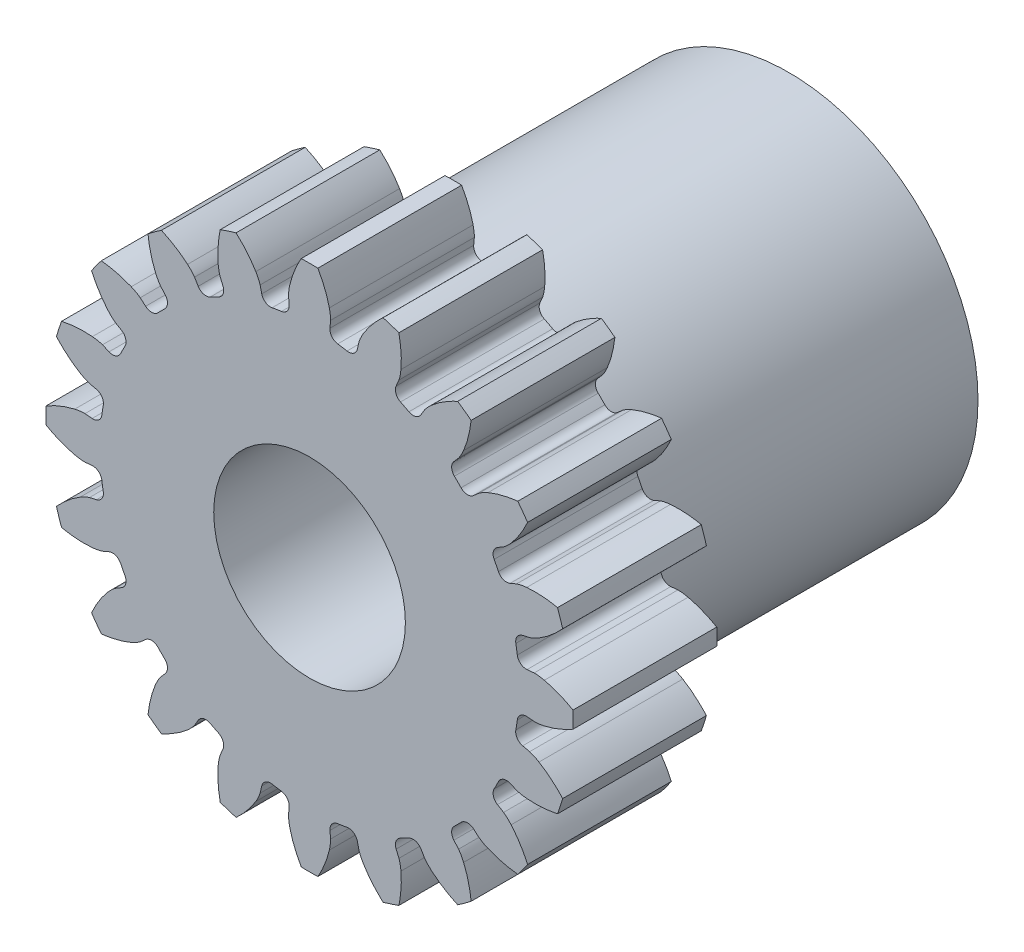
SolidWorks part; units mm, degrees
ref_plane "Front Plane" through (0, 0, 0) normal (0, 0, 1) x (1, 0, 0)
ref_plane "Top Plane" through (0, 0, 0) normal (0, 1, 0) x (1, 0, 0)
ref_plane "Right Plane" through (0, 0, 0) normal (1, 0, 0) x (0, 0, -1)
ref_plane "Plane1" through (0, 0, 0) normal (0, 0, -1) x (-1, 0, 0)
sketch "Sketch1" plane through (0, 0, 0) normal (0, 0, -1) x (-1, 0, 0)
  line L0 (-4.4476, -0.9979) -> (-4.5932, -1.031)
  line L1 (-4.3219, -1.8657) -> (-4.1847, -1.8069)
  line L2 (-3.9215, -2.3234) -> (-4.0498, -2.3999)
  line L3 (-3.5338, -3.11) -> (-3.4216, -3.0116)
  line L4 (-3.0116, -3.4216) -> (-3.11, -3.5338)
  line L5 (-2.3999, -4.0498) -> (-2.3234, -3.9215)
  line L6 (-1.8069, -4.1847) -> (-1.8657, -4.3219)
  line L7 (-1.031, -4.5932) -> (-0.9979, -4.4476)
  line L8 (-0.4253, -4.5383) -> (-0.4389, -4.6869)
  line L9 (0.4389, -4.6869) -> (0.4253, -4.5383)
  line L10 (0.9979, -4.4476) -> (1.031, -4.5932)
  line L11 (1.8657, -4.3219) -> (1.8069, -4.1847)
  line L12 (2.3234, -3.9215) -> (2.3999, -4.0498)
  line L13 (3.11, -3.5338) -> (3.0116, -3.4216)
  line L14 (3.4216, -3.0116) -> (3.5338, -3.11)
  line L15 (4.0498, -2.3999) -> (3.9215, -2.3234)
  line L16 (4.1847, -1.8069) -> (4.3219, -1.8657)
  line L17 (4.5932, -1.031) -> (4.4476, -0.9979)
  line L18 (4.5383, -0.4253) -> (4.6869, -0.4389)
  line L19 (4.6869, 0.4389) -> (4.5383, 0.4253)
  line L20 (4.4476, 0.9979) -> (4.5932, 1.031)
  line L21 (4.3219, 1.8657) -> (4.1847, 1.8069)
  line L22 (3.9215, 2.3234) -> (4.0498, 2.3999)
  line L23 (3.5338, 3.11) -> (3.4216, 3.0116)
  line L24 (3.0116, 3.4216) -> (3.11, 3.5338)
  line L25 (2.3999, 4.0498) -> (2.3234, 3.9215)
  line L26 (1.8069, 4.1847) -> (1.8657, 4.3219)
  line L27 (1.031, 4.5932) -> (0.9979, 4.4476)
  line L28 (0.4253, 4.5383) -> (0.4389, 4.6869)
  line L29 (-0.4389, 4.6869) -> (-0.4253, 4.5383)
  line L30 (-0.9979, 4.4476) -> (-1.031, 4.5932)
  line L31 (-1.8657, 4.3219) -> (-1.8069, 4.1847)
  line L32 (-2.3234, 3.9215) -> (-2.3999, 4.0498)
  line L33 (-3.11, 3.5338) -> (-3.0116, 3.4216)
  line L34 (-3.4216, 3.0116) -> (-3.5338, 3.11)
  line L35 (-4.0498, 2.3999) -> (-3.9215, 2.3234)
  line L36 (-4.1847, 1.8069) -> (-4.3219, 1.8657)
  line L37 (-4.5932, 1.031) -> (-4.4476, 0.9979)
  line L38 (-4.5383, 0.4253) -> (-4.6869, 0.4389)
  line L39 (-4.6869, -0.4389) -> (-4.5383, -0.4253)
  arc A0 (-4.3355, -0.5869) -> (-4.3046, -0.7816) centre (0, 0) ccw
  arc A1 (-4.3046, -0.7816) -> (-4.4476, -0.9979) centre (-4.4891, -0.8151) cw
  arc A2 (-5.2823, -1.5339) -> (-5.1751, -1.8639) centre (-0.0005, -0.0002) ccw
  arc A3 (-4.1847, -1.8069) -> (-3.9419, -1.8979) centre (-4.1108, -1.9792) cw
  arc A4 (-3.9419, -1.8979) -> (-3.8524, -2.0735) centre (0, 0) ccw
  arc A5 (-3.8524, -2.0735) -> (-3.9215, -2.3234) centre (-4.0175, -2.1624) cw
  arc A6 (-4.5498, -3.0912) -> (-4.3459, -3.3719) centre (-0.0004, -0.0003) ccw
  arc A7 (-3.4216, -3.0116) -> (-3.1625, -3.0231) centre (-3.298, -3.1527) cw
  arc A8 (-3.1625, -3.0231) -> (-3.0231, -3.1625) centre (0, 0) ccw
  arc A9 (-3.0231, -3.1625) -> (-3.0116, -3.4216) centre (-3.1527, -3.298) cw
  arc A10 (-3.3719, -4.3459) -> (-3.0912, -4.5498) centre (-0.0003, -0.0004) ccw
  arc A11 (-2.3234, -3.9215) -> (-2.0735, -3.8524) centre (-2.1624, -4.0175) cw
  arc A12 (-2.0735, -3.8524) -> (-1.8979, -3.9419) centre (0, 0) ccw
  arc A13 (-1.8979, -3.9419) -> (-1.8069, -4.1847) centre (-1.9792, -4.1108) cw
  arc A14 (-1.8639, -5.1751) -> (-1.5339, -5.2823) centre (-0.0002, -0.0005) ccw
  arc A15 (-0.9979, -4.4476) -> (-0.7816, -4.3046) centre (-0.8151, -4.4891) cw
  arc A16 (-0.7816, -4.3046) -> (-0.5869, -4.3355) centre (0, 0) ccw
  arc A17 (-0.5869, -4.3355) -> (-0.4253, -4.5383) centre (-0.612, -4.5213) cw
  arc A18 (-0.1735, -5.4978) -> (0.1735, -5.4978) centre (0, -0.0005) ccw
  arc A19 (0.4253, -4.5383) -> (0.5869, -4.3355) centre (0.612, -4.5213) cw
  arc A20 (0.5869, -4.3355) -> (0.7816, -4.3046) centre (0, 0) ccw
  arc A21 (0.7816, -4.3046) -> (0.9979, -4.4476) centre (0.8151, -4.4891) cw
  arc A22 (1.5339, -5.2823) -> (1.8639, -5.1751) centre (0.0002, -0.0005) ccw
  arc A23 (1.8069, -4.1847) -> (1.8979, -3.9419) centre (1.9792, -4.1108) cw
  arc A24 (1.8979, -3.9419) -> (2.0735, -3.8524) centre (0, 0) ccw
  arc A25 (2.0735, -3.8524) -> (2.3234, -3.9215) centre (2.1624, -4.0175) cw
  arc A26 (3.0912, -4.5498) -> (3.3719, -4.3459) centre (0.0003, -0.0004) ccw
  arc A27 (3.0116, -3.4216) -> (3.0231, -3.1625) centre (3.1527, -3.298) cw
  arc A28 (3.0231, -3.1625) -> (3.1625, -3.0231) centre (0, 0) ccw
  arc A29 (3.1625, -3.0231) -> (3.4216, -3.0116) centre (3.298, -3.1527) cw
  arc A30 (4.3459, -3.3719) -> (4.5498, -3.0912) centre (0.0004, -0.0003) ccw
  arc A31 (3.9215, -2.3234) -> (3.8524, -2.0735) centre (4.0175, -2.1624) cw
  arc A32 (3.8524, -2.0735) -> (3.9419, -1.8979) centre (0, 0) ccw
  arc A33 (3.9419, -1.8979) -> (4.1847, -1.8069) centre (4.1108, -1.9792) cw
  arc A34 (5.1751, -1.8639) -> (5.2823, -1.5339) centre (0.0005, -0.0002) ccw
  arc A35 (4.4476, -0.9979) -> (4.3046, -0.7816) centre (4.4891, -0.8151) cw
  arc A36 (4.3046, -0.7816) -> (4.3355, -0.5869) centre (0, 0) ccw
  arc A37 (4.3355, -0.5869) -> (4.5383, -0.4253) centre (4.5213, -0.612) cw
  arc A38 (5.4978, -0.1735) -> (5.4978, 0.1735) centre (0.0005, 0) ccw
  arc A39 (4.5383, 0.4253) -> (4.3355, 0.5869) centre (4.5213, 0.612) cw
  arc A40 (4.3355, 0.5869) -> (4.3046, 0.7816) centre (0, 0) ccw
  arc A41 (4.3046, 0.7816) -> (4.4476, 0.9979) centre (4.4891, 0.8151) cw
  arc A42 (5.2823, 1.5339) -> (5.1751, 1.8639) centre (0.0005, 0.0002) ccw
  arc A43 (4.1847, 1.8069) -> (3.9419, 1.8979) centre (4.1108, 1.9792) cw
  arc A44 (3.9419, 1.8979) -> (3.8524, 2.0735) centre (0, 0) ccw
  arc A45 (3.8524, 2.0735) -> (3.9215, 2.3234) centre (4.0175, 2.1624) cw
  arc A46 (4.5498, 3.0912) -> (4.3459, 3.3719) centre (0.0004, 0.0003) ccw
  arc A47 (3.4216, 3.0116) -> (3.1625, 3.0231) centre (3.298, 3.1527) cw
  arc A48 (3.1625, 3.0231) -> (3.0231, 3.1625) centre (0, 0) ccw
  arc A49 (3.0231, 3.1625) -> (3.0116, 3.4216) centre (3.1527, 3.298) cw
  arc A50 (3.3719, 4.3459) -> (3.0912, 4.5498) centre (0.0003, 0.0004) ccw
  arc A51 (2.3234, 3.9215) -> (2.0735, 3.8524) centre (2.1624, 4.0175) cw
  arc A52 (2.0735, 3.8524) -> (1.8979, 3.9419) centre (0, 0) ccw
  arc A53 (1.8979, 3.9419) -> (1.8069, 4.1847) centre (1.9792, 4.1108) cw
  arc A54 (1.8639, 5.1751) -> (1.5339, 5.2823) centre (0.0002, 0.0005) ccw
  arc A55 (0.9979, 4.4476) -> (0.7816, 4.3046) centre (0.8151, 4.4891) cw
  arc A56 (0.7816, 4.3046) -> (0.5869, 4.3355) centre (0, 0) ccw
  arc A57 (0.5869, 4.3355) -> (0.4253, 4.5383) centre (0.612, 4.5213) cw
  arc A58 (0.1735, 5.4978) -> (-0.1735, 5.4978) centre (0, 0.0005) ccw
  arc A59 (-0.4253, 4.5383) -> (-0.5869, 4.3355) centre (-0.612, 4.5213) cw
  arc A60 (-0.5869, 4.3355) -> (-0.7816, 4.3046) centre (0, 0) ccw
  arc A61 (-0.7816, 4.3046) -> (-0.9979, 4.4476) centre (-0.8151, 4.4891) cw
  arc A62 (-1.5339, 5.2823) -> (-1.8639, 5.1751) centre (-0.0002, 0.0005) ccw
  arc A63 (-1.8069, 4.1847) -> (-1.8979, 3.9419) centre (-1.9792, 4.1108) cw
  arc A64 (-1.8979, 3.9419) -> (-2.0735, 3.8524) centre (0, 0) ccw
  arc A65 (-2.0735, 3.8524) -> (-2.3234, 3.9215) centre (-2.1624, 4.0175) cw
  arc A66 (-3.0912, 4.5498) -> (-3.3719, 4.3459) centre (-0.0003, 0.0004) ccw
  arc A67 (-3.0116, 3.4216) -> (-3.0231, 3.1625) centre (-3.1527, 3.298) cw
  arc A68 (-3.0231, 3.1625) -> (-3.1625, 3.0231) centre (0, 0) ccw
  arc A69 (-3.1625, 3.0231) -> (-3.4216, 3.0116) centre (-3.298, 3.1527) cw
  arc A70 (-4.3459, 3.3719) -> (-4.5498, 3.0912) centre (-0.0004, 0.0003) ccw
  arc A71 (-3.9215, 2.3234) -> (-3.8524, 2.0735) centre (-4.0175, 2.1624) cw
  arc A72 (-3.8524, 2.0735) -> (-3.9419, 1.8979) centre (0, 0) ccw
  arc A73 (-3.9419, 1.8979) -> (-4.1847, 1.8069) centre (-4.1108, 1.9792) cw
  arc A74 (-5.1751, 1.8639) -> (-5.2823, 1.5339) centre (-0.0005, 0.0002) ccw
  arc A75 (-4.4476, 0.9979) -> (-4.3046, 0.7816) centre (-4.4891, 0.8151) cw
  arc A76 (-4.3046, 0.7816) -> (-4.3355, 0.5869) centre (0, 0) ccw
  arc A77 (-4.3355, 0.5869) -> (-4.5383, 0.4253) centre (-4.5213, 0.612) cw
  arc A78 (-5.4978, 0.1735) -> (-5.4978, -0.1735) centre (-0.0005, 0) ccw
  arc A79 (-4.5383, -0.4253) -> (-4.3355, -0.5869) centre (-4.5213, -0.612) cw
  spline S0 degree 3 poles (-4.5932, -1.031) (-4.6077, -1.0352) (-4.6221, -1.0404) (-4.6362, -1.0459) (-4.6624, -1.0562) (-4.6881, -1.068) (-4.7133, -1.0806) (-4.7387, -1.0933) (-4.7636, -1.1069) (-4.7881, -1.1212) knots 0 0 0 0 0.000046 0.000046 0.000046 0.00013 0.00013 0.00013 0.000215 0.000215 0.000215 0.000215
  spline S1 degree 3 poles (-4.7881, -1.1212) (-4.8505, -1.1578) (-4.9104, -1.1989) (-4.9678, -1.2429) (-5.0243, -1.2863) (-5.0786, -1.3326) (-5.1307, -1.3811) (-5.1833, -1.4299) (-5.2338, -1.4811) (-5.2823, -1.5339) knots 0 0 0 0 0.000217 0.000217 0.000217 0.000431 0.000431 0.000431 0.000646 0.000646 0.000646 0.000646
  spline S2 degree 3 poles (-5.1751, -1.8639) (-5.1043, -1.8782) (-5.0329, -1.89) (-4.9612, -1.8986) (-4.8905, -1.9071) (-4.8194, -1.9127) (-4.7483, -1.9145) (-4.6764, -1.9163) (-4.6042, -1.9144) (-4.5327, -1.9074) knots 0 0 0 0 0.000217 0.000217 0.000217 0.00043 0.00043 0.00043 0.000646 0.000646 0.000646 0.000646
  spline S3 degree 3 poles (-4.5327, -1.9074) (-4.5025, -1.9043) (-4.4723, -1.9004) (-4.4424, -1.8952) (-4.4221, -1.8918) (-4.4018, -1.8877) (-4.3817, -1.883) (-4.3616, -1.8782) (-4.3414, -1.8728) (-4.3219, -1.8657) knots 0 0 0 0 0.000091 0.000091 0.000091 0.000153 0.000153 0.000153 0.000215 0.000215 0.000215 0.000215
  spline S4 degree 3 poles (-4.0498, -2.3999) (-4.0623, -2.4084) (-4.0743, -2.4177) (-4.0861, -2.4274) (-4.1079, -2.4453) (-4.1286, -2.4644) (-4.1487, -2.4842) (-4.1689, -2.5041) (-4.1884, -2.5247) (-4.2073, -2.5459) knots 0 0 0 0 0.000046 0.000046 0.000046 0.00013 0.00013 0.00013 0.000215 0.000215 0.000215 0.000215
  spline S5 degree 3 poles (-4.2073, -2.5459) (-4.2554, -2.6) (-4.2996, -2.6576) (-4.3406, -2.7172) (-4.3809, -2.7759) (-4.4182, -2.8367) (-4.4528, -2.899) (-4.4877, -2.9617) (-4.5199, -3.0259) (-4.5498, -3.0912) knots 0 0 0 0 0.000217 0.000217 0.000217 0.000431 0.000431 0.000431 0.000646 0.000646 0.000646 0.000646
  spline S6 degree 3 poles (-4.3459, -3.3719) (-4.2741, -3.3636) (-4.2025, -3.3527) (-4.1316, -3.3388) (-4.0618, -3.325) (-3.9925, -3.3083) (-3.9243, -3.2881) (-3.8554, -3.2676) (-3.7873, -3.2435) (-3.7214, -3.2147) knots 0 0 0 0 0.000217 0.000217 0.000217 0.00043 0.00043 0.00043 0.000646 0.000646 0.000646 0.000646
  spline S7 degree 3 poles (-3.7214, -3.2147) (-3.6936, -3.2024) (-3.6662, -3.1894) (-3.6393, -3.1753) (-3.6211, -3.1657) (-3.603, -3.1556) (-3.5854, -3.1448) (-3.5677, -3.134) (-3.5502, -3.1227) (-3.5338, -3.11) knots 0 0 0 0 0.000091 0.000091 0.000091 0.000153 0.000153 0.000153 0.000215 0.000215 0.000215 0.000215
  spline S8 degree 3 poles (-3.11, -3.5338) (-3.1193, -3.5458) (-3.1278, -3.5584) (-3.136, -3.5712) (-3.1512, -3.595) (-3.165, -3.6196) (-3.178, -3.6446) (-3.1911, -3.6698) (-3.2032, -3.6955) (-3.2147, -3.7214) knots 0 0 0 0 0.000046 0.000046 0.000046 0.00013 0.00013 0.00013 0.000215 0.000215 0.000215 0.000215
  spline S9 degree 3 poles (-3.2147, -3.7214) (-3.2436, -3.7877) (-3.2679, -3.8562) (-3.2884, -3.9256) (-3.3087, -3.9938) (-3.3254, -4.0632) (-3.3391, -4.1331) (-3.3529, -4.2035) (-3.3637, -4.2746) (-3.3719, -4.3459) knots 0 0 0 0 0.000217 0.000217 0.000217 0.000431 0.000431 0.000431 0.000646 0.000646 0.000646 0.000646
  spline S10 degree 3 poles (-3.0912, -4.5498) (-3.0255, -4.5197) (-2.9608, -4.4873) (-2.8977, -4.4521) (-2.8355, -4.4175) (-2.7748, -4.3802) (-2.7162, -4.3398) (-2.6569, -4.299) (-2.5997, -4.2551) (-2.5459, -4.2073) knots 0 0 0 0 0.000217 0.000217 0.000217 0.00043 0.00043 0.00043 0.000646 0.000646 0.000646 0.000646
  spline S11 degree 3 poles (-2.5459, -4.2073) (-2.5233, -4.1871) (-2.5012, -4.1662) (-2.48, -4.1445) (-2.4656, -4.1297) (-2.4516, -4.1145) (-2.4381, -4.0989) (-2.4246, -4.0831) (-2.4115, -4.0669) (-2.3999, -4.0498) knots 0 0 0 0 0.000091 0.000091 0.000091 0.000153 0.000153 0.000153 0.000215 0.000215 0.000215 0.000215
  spline S12 degree 3 poles (-1.8657, -4.3219) (-1.8709, -4.3362) (-1.8751, -4.3508) (-1.8789, -4.3655) (-1.886, -4.3928) (-1.8916, -4.4205) (-1.8962, -4.4483) (-1.9009, -4.4763) (-1.9045, -4.5045) (-1.9074, -4.5327) knots 0 0 0 0 0.000046 0.000046 0.000046 0.00013 0.00013 0.00013 0.000215 0.000215 0.000215 0.000215
  spline S13 degree 3 poles (-1.9074, -4.5327) (-1.9144, -4.6047) (-1.9163, -4.6773) (-1.9144, -4.7496) (-1.9126, -4.8208) (-1.907, -4.8919) (-1.8984, -4.9626) (-1.8898, -5.0339) (-1.8781, -5.1048) (-1.8639, -5.1751) knots 0 0 0 0 0.000217 0.000217 0.000217 0.000431 0.000431 0.000431 0.000646 0.000646 0.000646 0.000646
  spline S14 degree 3 poles (-1.5339, -5.2823) (-1.4807, -5.2335) (-1.4292, -5.1826) (-1.3801, -5.1297) (-1.3317, -5.0775) (-1.2854, -5.0232) (-1.2421, -4.9668) (-1.1984, -4.9097) (-1.1575, -4.8502) (-1.1212, -4.7881) knots 0 0 0 0 0.000217 0.000217 0.000217 0.00043 0.00043 0.00043 0.000646 0.000646 0.000646 0.000646
  spline S15 degree 3 poles (-1.1212, -4.7881) (-1.1059, -4.7619) (-1.0914, -4.7352) (-1.0779, -4.708) (-1.0688, -4.6895) (-1.0601, -4.6707) (-1.0522, -4.6517) (-1.0442, -4.6325) (-1.0367, -4.6131) (-1.031, -4.5932) knots 0 0 0 0 0.000091 0.000091 0.000091 0.000153 0.000153 0.000153 0.000215 0.000215 0.000215 0.000215
  spline S16 degree 3 poles (-0.4389, -4.6869) (-0.4394, -4.7021) (-0.4389, -4.7173) (-0.438, -4.7325) (-0.4363, -4.7606) (-0.433, -4.7887) (-0.4288, -4.8166) (-0.4246, -4.8446) (-0.4193, -4.8725) (-0.4133, -4.9002) knots 0 0 0 0 0.000046 0.000046 0.000046 0.00013 0.00013 0.00013 0.000215 0.000215 0.000215 0.000215
  spline S17 degree 3 poles (-0.4133, -4.9002) (-0.3978, -4.9709) (-0.3772, -5.0405) (-0.353, -5.1087) (-0.3293, -5.1759) (-0.302, -5.2418) (-0.272, -5.3064) (-0.2418, -5.3715) (-0.2087, -5.4353) (-0.1735, -5.4978) knots 0 0 0 0 0.000217 0.000217 0.000217 0.000431 0.000431 0.000431 0.000646 0.000646 0.000646 0.000646
  spline S18 degree 3 poles (0.1735, -5.4978) (0.209, -5.4349) (0.2422, -5.3706) (0.2726, -5.3051) (0.3025, -5.2405) (0.3298, -5.1746) (0.3535, -5.1075) (0.3774, -5.0397) (0.3979, -4.9705) (0.4133, -4.9002) knots 0 0 0 0 0.000217 0.000217 0.000217 0.00043 0.00043 0.00043 0.000646 0.000646 0.000646 0.000646
  spline S19 degree 3 poles (0.4133, -4.9002) (0.4198, -4.8706) (0.4253, -4.8407) (0.4297, -4.8107) (0.4327, -4.7902) (0.4351, -4.7697) (0.4368, -4.7492) (0.4385, -4.7285) (0.4395, -4.7077) (0.4389, -4.6869) knots 0 0 0 0 0.000091 0.000091 0.000091 0.000153 0.000153 0.000153 0.000215 0.000215 0.000215 0.000215
  spline S20 degree 3 poles (1.031, -4.5932) (1.0352, -4.6077) (1.0404, -4.6221) (1.0459, -4.6362) (1.0562, -4.6624) (1.068, -4.6881) (1.0806, -4.7133) (1.0933, -4.7387) (1.1069, -4.7636) (1.1212, -4.7881) knots 0 0 0 0 0.000046 0.000046 0.000046 0.00013 0.00013 0.00013 0.000215 0.000215 0.000215 0.000215
  spline S21 degree 3 poles (1.1212, -4.7881) (1.1578, -4.8505) (1.1989, -4.9104) (1.2429, -4.9678) (1.2863, -5.0243) (1.3326, -5.0786) (1.3811, -5.1307) (1.4299, -5.1833) (1.4811, -5.2338) (1.5339, -5.2823) knots 0 0 0 0 0.000217 0.000217 0.000217 0.000431 0.000431 0.000431 0.000646 0.000646 0.000646 0.000646
  spline S22 degree 3 poles (1.8639, -5.1751) (1.8782, -5.1043) (1.89, -5.0329) (1.8986, -4.9612) (1.9071, -4.8905) (1.9127, -4.8194) (1.9145, -4.7483) (1.9163, -4.6764) (1.9144, -4.6042) (1.9074, -4.5327) knots 0 0 0 0 0.000217 0.000217 0.000217 0.00043 0.00043 0.00043 0.000646 0.000646 0.000646 0.000646
  spline S23 degree 3 poles (1.9074, -4.5327) (1.9043, -4.5025) (1.9004, -4.4723) (1.8952, -4.4424) (1.8918, -4.4221) (1.8877, -4.4018) (1.883, -4.3817) (1.8782, -4.3616) (1.8728, -4.3414) (1.8657, -4.3219) knots 0 0 0 0 0.000091 0.000091 0.000091 0.000153 0.000153 0.000153 0.000215 0.000215 0.000215 0.000215
  spline S24 degree 3 poles (2.3999, -4.0498) (2.4084, -4.0623) (2.4177, -4.0743) (2.4274, -4.0861) (2.4453, -4.1079) (2.4644, -4.1286) (2.4842, -4.1487) (2.5041, -4.1689) (2.5247, -4.1884) (2.5459, -4.2073) knots 0 0 0 0 0.000046 0.000046 0.000046 0.00013 0.00013 0.00013 0.000215 0.000215 0.000215 0.000215
  spline S25 degree 3 poles (2.5459, -4.2073) (2.6, -4.2554) (2.6576, -4.2996) (2.7172, -4.3406) (2.7759, -4.3809) (2.8367, -4.4182) (2.899, -4.4528) (2.9617, -4.4877) (3.0259, -4.5199) (3.0912, -4.5498) knots 0 0 0 0 0.000217 0.000217 0.000217 0.000431 0.000431 0.000431 0.000646 0.000646 0.000646 0.000646
  spline S26 degree 3 poles (3.3719, -4.3459) (3.3636, -4.2741) (3.3527, -4.2025) (3.3388, -4.1316) (3.325, -4.0618) (3.3083, -3.9925) (3.2881, -3.9243) (3.2676, -3.8554) (3.2435, -3.7873) (3.2147, -3.7214) knots 0 0 0 0 0.000217 0.000217 0.000217 0.00043 0.00043 0.00043 0.000646 0.000646 0.000646 0.000646
  spline S27 degree 3 poles (3.2147, -3.7214) (3.2024, -3.6936) (3.1894, -3.6662) (3.1753, -3.6393) (3.1657, -3.6211) (3.1556, -3.603) (3.1448, -3.5854) (3.134, -3.5677) (3.1227, -3.5502) (3.11, -3.5338) knots 0 0 0 0 0.000091 0.000091 0.000091 0.000153 0.000153 0.000153 0.000215 0.000215 0.000215 0.000215
  spline S28 degree 3 poles (3.5338, -3.11) (3.5458, -3.1193) (3.5584, -3.1278) (3.5712, -3.136) (3.595, -3.1512) (3.6196, -3.165) (3.6446, -3.178) (3.6698, -3.1911) (3.6955, -3.2032) (3.7214, -3.2147) knots 0 0 0 0 0.000046 0.000046 0.000046 0.00013 0.00013 0.00013 0.000215 0.000215 0.000215 0.000215
  spline S29 degree 3 poles (3.7214, -3.2147) (3.7877, -3.2436) (3.8562, -3.2679) (3.9256, -3.2884) (3.9938, -3.3087) (4.0632, -3.3254) (4.1331, -3.3391) (4.2035, -3.3529) (4.2746, -3.3637) (4.3459, -3.3719) knots 0 0 0 0 0.000217 0.000217 0.000217 0.000431 0.000431 0.000431 0.000646 0.000646 0.000646 0.000646
  spline S30 degree 3 poles (4.5498, -3.0912) (4.5197, -3.0255) (4.4873, -2.9608) (4.4521, -2.8977) (4.4175, -2.8355) (4.3802, -2.7748) (4.3398, -2.7162) (4.299, -2.6569) (4.2551, -2.5997) (4.2073, -2.5459) knots 0 0 0 0 0.000217 0.000217 0.000217 0.00043 0.00043 0.00043 0.000646 0.000646 0.000646 0.000646
  spline S31 degree 3 poles (4.2073, -2.5459) (4.1871, -2.5233) (4.1662, -2.5012) (4.1445, -2.48) (4.1297, -2.4656) (4.1145, -2.4516) (4.0989, -2.4381) (4.0831, -2.4246) (4.0669, -2.4115) (4.0498, -2.3999) knots 0 0 0 0 0.000091 0.000091 0.000091 0.000153 0.000153 0.000153 0.000215 0.000215 0.000215 0.000215
  spline S32 degree 3 poles (4.3219, -1.8657) (4.3362, -1.8709) (4.3508, -1.8751) (4.3655, -1.8789) (4.3928, -1.886) (4.4205, -1.8916) (4.4483, -1.8962) (4.4763, -1.9009) (4.5045, -1.9045) (4.5327, -1.9074) knots 0 0 0 0 0.000046 0.000046 0.000046 0.00013 0.00013 0.00013 0.000215 0.000215 0.000215 0.000215
  spline S33 degree 3 poles (4.5327, -1.9074) (4.6047, -1.9144) (4.6773, -1.9163) (4.7496, -1.9144) (4.8208, -1.9126) (4.8919, -1.907) (4.9626, -1.8984) (5.0339, -1.8898) (5.1048, -1.8781) (5.1751, -1.8639) knots 0 0 0 0 0.000217 0.000217 0.000217 0.000431 0.000431 0.000431 0.000646 0.000646 0.000646 0.000646
  spline S34 degree 3 poles (5.2823, -1.5339) (5.2335, -1.4807) (5.1826, -1.4292) (5.1297, -1.3801) (5.0775, -1.3317) (5.0232, -1.2854) (4.9668, -1.2421) (4.9097, -1.1984) (4.8502, -1.1575) (4.7881, -1.1212) knots 0 0 0 0 0.000217 0.000217 0.000217 0.00043 0.00043 0.00043 0.000646 0.000646 0.000646 0.000646
  spline S35 degree 3 poles (4.7881, -1.1212) (4.7619, -1.1059) (4.7352, -1.0914) (4.708, -1.0779) (4.6895, -1.0688) (4.6707, -1.0601) (4.6517, -1.0522) (4.6325, -1.0442) (4.6131, -1.0367) (4.5932, -1.031) knots 0 0 0 0 0.000091 0.000091 0.000091 0.000153 0.000153 0.000153 0.000215 0.000215 0.000215 0.000215
  spline S36 degree 3 poles (4.6869, -0.4389) (4.7021, -0.4394) (4.7173, -0.4389) (4.7325, -0.438) (4.7606, -0.4363) (4.7887, -0.433) (4.8166, -0.4288) (4.8446, -0.4246) (4.8725, -0.4193) (4.9002, -0.4133) knots 0 0 0 0 0.000046 0.000046 0.000046 0.00013 0.00013 0.00013 0.000215 0.000215 0.000215 0.000215
  spline S37 degree 3 poles (4.9002, -0.4133) (4.9709, -0.3978) (5.0405, -0.3772) (5.1087, -0.353) (5.1759, -0.3293) (5.2418, -0.302) (5.3064, -0.272) (5.3715, -0.2418) (5.4353, -0.2087) (5.4978, -0.1735) knots 0 0 0 0 0.000217 0.000217 0.000217 0.000431 0.000431 0.000431 0.000646 0.000646 0.000646 0.000646
  spline S38 degree 3 poles (5.4978, 0.1735) (5.4349, 0.209) (5.3706, 0.2422) (5.3051, 0.2726) (5.2405, 0.3025) (5.1746, 0.3298) (5.1075, 0.3535) (5.0397, 0.3774) (4.9705, 0.3979) (4.9002, 0.4133) knots 0 0 0 0 0.000217 0.000217 0.000217 0.00043 0.00043 0.00043 0.000646 0.000646 0.000646 0.000646
  spline S39 degree 3 poles (4.9002, 0.4133) (4.8706, 0.4198) (4.8407, 0.4253) (4.8107, 0.4297) (4.7902, 0.4327) (4.7697, 0.4351) (4.7492, 0.4368) (4.7285, 0.4385) (4.7077, 0.4395) (4.6869, 0.4389) knots 0 0 0 0 0.000091 0.000091 0.000091 0.000153 0.000153 0.000153 0.000215 0.000215 0.000215 0.000215
  spline S40 degree 3 poles (4.5932, 1.031) (4.6077, 1.0352) (4.6221, 1.0404) (4.6362, 1.0459) (4.6624, 1.0562) (4.6881, 1.068) (4.7133, 1.0806) (4.7387, 1.0933) (4.7636, 1.1069) (4.7881, 1.1212) knots 0 0 0 0 0.000046 0.000046 0.000046 0.00013 0.00013 0.00013 0.000215 0.000215 0.000215 0.000215
  spline S41 degree 3 poles (4.7881, 1.1212) (4.8505, 1.1578) (4.9104, 1.1989) (4.9678, 1.2429) (5.0243, 1.2863) (5.0786, 1.3326) (5.1307, 1.3811) (5.1833, 1.4299) (5.2338, 1.4811) (5.2823, 1.5339) knots 0 0 0 0 0.000217 0.000217 0.000217 0.000431 0.000431 0.000431 0.000646 0.000646 0.000646 0.000646
  spline S42 degree 3 poles (5.1751, 1.8639) (5.1043, 1.8782) (5.0329, 1.89) (4.9612, 1.8986) (4.8905, 1.9071) (4.8194, 1.9127) (4.7483, 1.9145) (4.6764, 1.9163) (4.6042, 1.9144) (4.5327, 1.9074) knots 0 0 0 0 0.000217 0.000217 0.000217 0.00043 0.00043 0.00043 0.000646 0.000646 0.000646 0.000646
  spline S43 degree 3 poles (4.5327, 1.9074) (4.5025, 1.9043) (4.4723, 1.9004) (4.4424, 1.8952) (4.4221, 1.8918) (4.4018, 1.8877) (4.3817, 1.883) (4.3616, 1.8782) (4.3414, 1.8728) (4.3219, 1.8657) knots 0 0 0 0 0.000091 0.000091 0.000091 0.000153 0.000153 0.000153 0.000215 0.000215 0.000215 0.000215
  spline S44 degree 3 poles (4.0498, 2.3999) (4.0623, 2.4084) (4.0743, 2.4177) (4.0861, 2.4274) (4.1079, 2.4453) (4.1286, 2.4644) (4.1487, 2.4842) (4.1689, 2.5041) (4.1884, 2.5247) (4.2073, 2.5459) knots 0 0 0 0 0.000046 0.000046 0.000046 0.00013 0.00013 0.00013 0.000215 0.000215 0.000215 0.000215
  spline S45 degree 3 poles (4.2073, 2.5459) (4.2554, 2.6) (4.2996, 2.6576) (4.3406, 2.7172) (4.3809, 2.7759) (4.4182, 2.8367) (4.4528, 2.899) (4.4877, 2.9617) (4.5199, 3.0259) (4.5498, 3.0912) knots 0 0 0 0 0.000217 0.000217 0.000217 0.000431 0.000431 0.000431 0.000646 0.000646 0.000646 0.000646
  spline S46 degree 3 poles (4.3459, 3.3719) (4.2741, 3.3636) (4.2025, 3.3527) (4.1316, 3.3388) (4.0618, 3.325) (3.9925, 3.3083) (3.9243, 3.2881) (3.8554, 3.2676) (3.7873, 3.2435) (3.7214, 3.2147) knots 0 0 0 0 0.000217 0.000217 0.000217 0.00043 0.00043 0.00043 0.000646 0.000646 0.000646 0.000646
  spline S47 degree 3 poles (3.7214, 3.2147) (3.6936, 3.2024) (3.6662, 3.1894) (3.6393, 3.1753) (3.6211, 3.1657) (3.603, 3.1556) (3.5854, 3.1448) (3.5677, 3.134) (3.5502, 3.1227) (3.5338, 3.11) knots 0 0 0 0 0.000091 0.000091 0.000091 0.000153 0.000153 0.000153 0.000215 0.000215 0.000215 0.000215
  spline S48 degree 3 poles (3.11, 3.5338) (3.1193, 3.5458) (3.1278, 3.5584) (3.136, 3.5712) (3.1512, 3.595) (3.165, 3.6196) (3.178, 3.6446) (3.1911, 3.6698) (3.2032, 3.6955) (3.2147, 3.7214) knots 0 0 0 0 0.000046 0.000046 0.000046 0.00013 0.00013 0.00013 0.000215 0.000215 0.000215 0.000215
  spline S49 degree 3 poles (3.2147, 3.7214) (3.2436, 3.7877) (3.2679, 3.8562) (3.2884, 3.9256) (3.3087, 3.9938) (3.3254, 4.0632) (3.3391, 4.1331) (3.3529, 4.2035) (3.3637, 4.2746) (3.3719, 4.3459) knots 0 0 0 0 0.000217 0.000217 0.000217 0.000431 0.000431 0.000431 0.000646 0.000646 0.000646 0.000646
  spline S50 degree 3 poles (3.0912, 4.5498) (3.0255, 4.5197) (2.9608, 4.4873) (2.8977, 4.4521) (2.8355, 4.4175) (2.7748, 4.3802) (2.7162, 4.3398) (2.6569, 4.299) (2.5997, 4.2551) (2.5459, 4.2073) knots 0 0 0 0 0.000217 0.000217 0.000217 0.00043 0.00043 0.00043 0.000646 0.000646 0.000646 0.000646
  spline S51 degree 3 poles (2.5459, 4.2073) (2.5233, 4.1871) (2.5012, 4.1662) (2.48, 4.1445) (2.4656, 4.1297) (2.4516, 4.1145) (2.4381, 4.0989) (2.4246, 4.0831) (2.4115, 4.0669) (2.3999, 4.0498) knots 0 0 0 0 0.000091 0.000091 0.000091 0.000153 0.000153 0.000153 0.000215 0.000215 0.000215 0.000215
  spline S52 degree 3 poles (1.8657, 4.3219) (1.8709, 4.3362) (1.8751, 4.3508) (1.8789, 4.3655) (1.886, 4.3928) (1.8916, 4.4205) (1.8962, 4.4483) (1.9009, 4.4763) (1.9045, 4.5045) (1.9074, 4.5327) knots 0 0 0 0 0.000046 0.000046 0.000046 0.00013 0.00013 0.00013 0.000215 0.000215 0.000215 0.000215
  spline S53 degree 3 poles (1.9074, 4.5327) (1.9144, 4.6047) (1.9163, 4.6773) (1.9144, 4.7496) (1.9126, 4.8208) (1.907, 4.8919) (1.8984, 4.9626) (1.8898, 5.0339) (1.8781, 5.1048) (1.8639, 5.1751) knots 0 0 0 0 0.000217 0.000217 0.000217 0.000431 0.000431 0.000431 0.000646 0.000646 0.000646 0.000646
  spline S54 degree 3 poles (1.5339, 5.2823) (1.4807, 5.2335) (1.4292, 5.1826) (1.3801, 5.1297) (1.3317, 5.0775) (1.2854, 5.0232) (1.2421, 4.9668) (1.1984, 4.9097) (1.1575, 4.8502) (1.1212, 4.7881) knots 0 0 0 0 0.000217 0.000217 0.000217 0.00043 0.00043 0.00043 0.000646 0.000646 0.000646 0.000646
  spline S55 degree 3 poles (1.1212, 4.7881) (1.1059, 4.7619) (1.0914, 4.7352) (1.0779, 4.708) (1.0688, 4.6895) (1.0601, 4.6707) (1.0522, 4.6517) (1.0442, 4.6325) (1.0367, 4.6131) (1.031, 4.5932) knots 0 0 0 0 0.000091 0.000091 0.000091 0.000153 0.000153 0.000153 0.000215 0.000215 0.000215 0.000215
  spline S56 degree 3 poles (0.4389, 4.6869) (0.4394, 4.7021) (0.4389, 4.7173) (0.438, 4.7325) (0.4363, 4.7606) (0.433, 4.7887) (0.4288, 4.8166) (0.4246, 4.8446) (0.4193, 4.8725) (0.4133, 4.9002) knots 0 0 0 0 0.000046 0.000046 0.000046 0.00013 0.00013 0.00013 0.000215 0.000215 0.000215 0.000215
  spline S57 degree 3 poles (0.4133, 4.9002) (0.3978, 4.9709) (0.3772, 5.0405) (0.353, 5.1087) (0.3293, 5.1759) (0.302, 5.2418) (0.272, 5.3064) (0.2418, 5.3715) (0.2087, 5.4353) (0.1735, 5.4978) knots 0 0 0 0 0.000217 0.000217 0.000217 0.000431 0.000431 0.000431 0.000646 0.000646 0.000646 0.000646
  spline S58 degree 3 poles (-0.1735, 5.4978) (-0.209, 5.4349) (-0.2422, 5.3706) (-0.2726, 5.3051) (-0.3025, 5.2405) (-0.3298, 5.1746) (-0.3535, 5.1075) (-0.3774, 5.0397) (-0.3979, 4.9705) (-0.4133, 4.9002) knots 0 0 0 0 0.000217 0.000217 0.000217 0.00043 0.00043 0.00043 0.000646 0.000646 0.000646 0.000646
  spline S59 degree 3 poles (-0.4133, 4.9002) (-0.4198, 4.8706) (-0.4253, 4.8407) (-0.4297, 4.8107) (-0.4327, 4.7902) (-0.4351, 4.7697) (-0.4368, 4.7492) (-0.4385, 4.7285) (-0.4395, 4.7077) (-0.4389, 4.6869) knots 0 0 0 0 0.000091 0.000091 0.000091 0.000153 0.000153 0.000153 0.000215 0.000215 0.000215 0.000215
  spline S60 degree 3 poles (-1.031, 4.5932) (-1.0352, 4.6077) (-1.0404, 4.6221) (-1.0459, 4.6362) (-1.0562, 4.6624) (-1.068, 4.6881) (-1.0806, 4.7133) (-1.0933, 4.7387) (-1.1069, 4.7636) (-1.1212, 4.7881) knots 0 0 0 0 0.000046 0.000046 0.000046 0.00013 0.00013 0.00013 0.000215 0.000215 0.000215 0.000215
  spline S61 degree 3 poles (-1.1212, 4.7881) (-1.1578, 4.8505) (-1.1989, 4.9104) (-1.2429, 4.9678) (-1.2863, 5.0243) (-1.3326, 5.0786) (-1.3811, 5.1307) (-1.4299, 5.1833) (-1.4811, 5.2338) (-1.5339, 5.2823) knots 0 0 0 0 0.000217 0.000217 0.000217 0.000431 0.000431 0.000431 0.000646 0.000646 0.000646 0.000646
  spline S62 degree 3 poles (-1.8639, 5.1751) (-1.8782, 5.1043) (-1.89, 5.0329) (-1.8986, 4.9612) (-1.9071, 4.8905) (-1.9127, 4.8194) (-1.9145, 4.7483) (-1.9163, 4.6764) (-1.9144, 4.6042) (-1.9074, 4.5327) knots 0 0 0 0 0.000217 0.000217 0.000217 0.00043 0.00043 0.00043 0.000646 0.000646 0.000646 0.000646
  spline S63 degree 3 poles (-1.9074, 4.5327) (-1.9043, 4.5025) (-1.9004, 4.4723) (-1.8952, 4.4424) (-1.8918, 4.4221) (-1.8877, 4.4018) (-1.883, 4.3817) (-1.8782, 4.3616) (-1.8728, 4.3414) (-1.8657, 4.3219) knots 0 0 0 0 0.000091 0.000091 0.000091 0.000153 0.000153 0.000153 0.000215 0.000215 0.000215 0.000215
  spline S64 degree 3 poles (-2.3999, 4.0498) (-2.4084, 4.0623) (-2.4177, 4.0743) (-2.4274, 4.0861) (-2.4453, 4.1079) (-2.4644, 4.1286) (-2.4842, 4.1487) (-2.5041, 4.1689) (-2.5247, 4.1884) (-2.5459, 4.2073) knots 0 0 0 0 0.000046 0.000046 0.000046 0.00013 0.00013 0.00013 0.000215 0.000215 0.000215 0.000215
  spline S65 degree 3 poles (-2.5459, 4.2073) (-2.6, 4.2554) (-2.6576, 4.2996) (-2.7172, 4.3406) (-2.7759, 4.3809) (-2.8367, 4.4182) (-2.899, 4.4528) (-2.9617, 4.4877) (-3.0259, 4.5199) (-3.0912, 4.5498) knots 0 0 0 0 0.000217 0.000217 0.000217 0.000431 0.000431 0.000431 0.000646 0.000646 0.000646 0.000646
  spline S66 degree 3 poles (-3.3719, 4.3459) (-3.3636, 4.2741) (-3.3527, 4.2025) (-3.3388, 4.1316) (-3.325, 4.0618) (-3.3083, 3.9925) (-3.2881, 3.9243) (-3.2676, 3.8554) (-3.2435, 3.7873) (-3.2147, 3.7214) knots 0 0 0 0 0.000217 0.000217 0.000217 0.00043 0.00043 0.00043 0.000646 0.000646 0.000646 0.000646
  spline S67 degree 3 poles (-3.2147, 3.7214) (-3.2024, 3.6936) (-3.1894, 3.6662) (-3.1753, 3.6393) (-3.1657, 3.6211) (-3.1556, 3.603) (-3.1448, 3.5854) (-3.134, 3.5677) (-3.1227, 3.5502) (-3.11, 3.5338) knots 0 0 0 0 0.000091 0.000091 0.000091 0.000153 0.000153 0.000153 0.000215 0.000215 0.000215 0.000215
  spline S68 degree 3 poles (-3.5338, 3.11) (-3.5458, 3.1193) (-3.5584, 3.1278) (-3.5712, 3.136) (-3.595, 3.1512) (-3.6196, 3.165) (-3.6446, 3.178) (-3.6698, 3.1911) (-3.6955, 3.2032) (-3.7214, 3.2147) knots 0 0 0 0 0.000046 0.000046 0.000046 0.00013 0.00013 0.00013 0.000215 0.000215 0.000215 0.000215
  spline S69 degree 3 poles (-3.7214, 3.2147) (-3.7877, 3.2436) (-3.8562, 3.2679) (-3.9256, 3.2884) (-3.9938, 3.3087) (-4.0632, 3.3254) (-4.1331, 3.3391) (-4.2035, 3.3529) (-4.2746, 3.3637) (-4.3459, 3.3719) knots 0 0 0 0 0.000217 0.000217 0.000217 0.000431 0.000431 0.000431 0.000646 0.000646 0.000646 0.000646
  spline S70 degree 3 poles (-4.5498, 3.0912) (-4.5197, 3.0255) (-4.4873, 2.9608) (-4.4521, 2.8977) (-4.4175, 2.8355) (-4.3802, 2.7748) (-4.3398, 2.7162) (-4.299, 2.6569) (-4.2551, 2.5997) (-4.2073, 2.5459) knots 0 0 0 0 0.000217 0.000217 0.000217 0.00043 0.00043 0.00043 0.000646 0.000646 0.000646 0.000646
  spline S71 degree 3 poles (-4.2073, 2.5459) (-4.1871, 2.5233) (-4.1662, 2.5012) (-4.1445, 2.48) (-4.1297, 2.4656) (-4.1145, 2.4516) (-4.0989, 2.4381) (-4.0831, 2.4246) (-4.0669, 2.4115) (-4.0498, 2.3999) knots 0 0 0 0 0.000091 0.000091 0.000091 0.000153 0.000153 0.000153 0.000215 0.000215 0.000215 0.000215
  spline S72 degree 3 poles (-4.3219, 1.8657) (-4.3362, 1.8709) (-4.3508, 1.8751) (-4.3655, 1.8789) (-4.3928, 1.886) (-4.4205, 1.8916) (-4.4483, 1.8962) (-4.4763, 1.9009) (-4.5045, 1.9045) (-4.5327, 1.9074) knots 0 0 0 0 0.000046 0.000046 0.000046 0.00013 0.00013 0.00013 0.000215 0.000215 0.000215 0.000215
  spline S73 degree 3 poles (-4.5327, 1.9074) (-4.6047, 1.9144) (-4.6773, 1.9163) (-4.7496, 1.9144) (-4.8208, 1.9126) (-4.8919, 1.907) (-4.9626, 1.8984) (-5.0339, 1.8898) (-5.1048, 1.8781) (-5.1751, 1.8639) knots 0 0 0 0 0.000217 0.000217 0.000217 0.000431 0.000431 0.000431 0.000646 0.000646 0.000646 0.000646
  spline S74 degree 3 poles (-5.2823, 1.5339) (-5.2335, 1.4807) (-5.1826, 1.4292) (-5.1297, 1.3801) (-5.0775, 1.3317) (-5.0232, 1.2854) (-4.9668, 1.2421) (-4.9097, 1.1984) (-4.8502, 1.1575) (-4.7881, 1.1212) knots 0 0 0 0 0.000217 0.000217 0.000217 0.00043 0.00043 0.00043 0.000646 0.000646 0.000646 0.000646
  spline S75 degree 3 poles (-4.7881, 1.1212) (-4.7619, 1.1059) (-4.7352, 1.0914) (-4.708, 1.0779) (-4.6895, 1.0688) (-4.6707, 1.0601) (-4.6517, 1.0522) (-4.6325, 1.0442) (-4.6131, 1.0367) (-4.5932, 1.031) knots 0 0 0 0 0.000091 0.000091 0.000091 0.000153 0.000153 0.000153 0.000215 0.000215 0.000215 0.000215
  spline S76 degree 3 poles (-4.6869, 0.4389) (-4.7021, 0.4394) (-4.7173, 0.4389) (-4.7325, 0.438) (-4.7606, 0.4363) (-4.7887, 0.433) (-4.8166, 0.4288) (-4.8446, 0.4246) (-4.8725, 0.4193) (-4.9002, 0.4133) knots 0 0 0 0 0.000046 0.000046 0.000046 0.00013 0.00013 0.00013 0.000215 0.000215 0.000215 0.000215
  spline S77 degree 3 poles (-4.9002, 0.4133) (-4.9709, 0.3978) (-5.0405, 0.3772) (-5.1087, 0.353) (-5.1759, 0.3293) (-5.2418, 0.302) (-5.3064, 0.272) (-5.3715, 0.2418) (-5.4353, 0.2087) (-5.4978, 0.1735) knots 0 0 0 0 0.000217 0.000217 0.000217 0.000431 0.000431 0.000431 0.000646 0.000646 0.000646 0.000646
  spline S78 degree 3 poles (-5.4978, -0.1735) (-5.4349, -0.209) (-5.3706, -0.2422) (-5.3051, -0.2726) (-5.2405, -0.3025) (-5.1746, -0.3298) (-5.1075, -0.3535) (-5.0397, -0.3774) (-4.9705, -0.3979) (-4.9002, -0.4133) knots 0 0 0 0 0.000217 0.000217 0.000217 0.00043 0.00043 0.00043 0.000646 0.000646 0.000646 0.000646
  spline S79 degree 3 poles (-4.9002, -0.4133) (-4.8706, -0.4198) (-4.8407, -0.4253) (-4.8107, -0.4297) (-4.7902, -0.4327) (-4.7697, -0.4351) (-4.7492, -0.4368) (-4.7285, -0.4385) (-4.7077, -0.4395) (-4.6869, -0.4389) knots 0 0 0 0 0.000091 0.000091 0.000091 0.000153 0.000153 0.000153 0.000215 0.000215 0.000215 0.000215
extrude "Gear" add sketch "Sketch1" against normal blind 3
sketch "Sketch2" plane through (0, 0, 0) normal (0, 0, -1) x (-1, 0, 0)
  circle A0 centre (0, 0) radius 2
  dimension "D1" = 4
extrude "Cut-Extrude1" cut sketch "Sketch2" against normal through all
sketch "Sketch3" plane through (0, 0, 0) normal (0, 0, -1) x (-1, 0, 0)
  circle A0 centre (0, 0) radius 3.95
  circle A1 centre (0, 0) radius 2 construction
  circle A2 centre (0, 0) radius 2
  dimension "D1" = 7.9
extrude "Boss-Extrude2" add sketch "Sketch3" along normal blind 7
